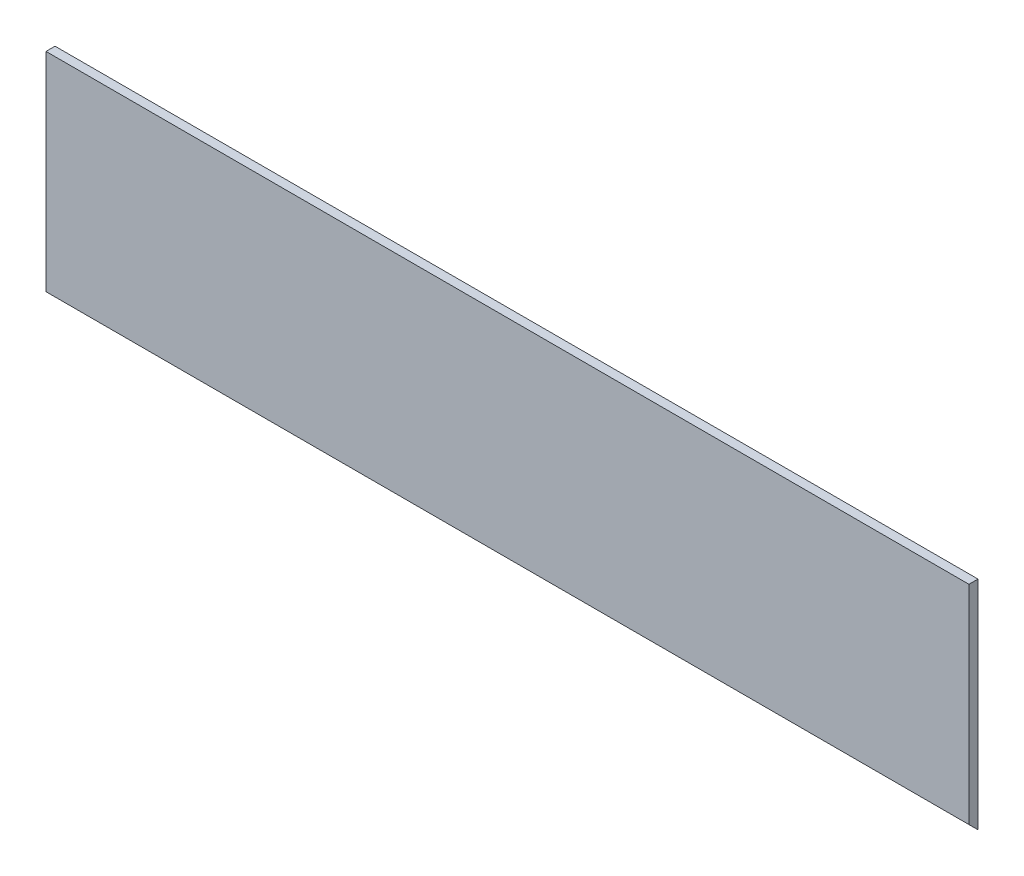
SolidWorks part; units mm, degrees
ref_plane "前视基准面" through (0, 0, 0) normal (0, 0, 1) x (1, 0, 0)
ref_plane "上视基准面" through (0, 0, 0) normal (0, 1, 0) x (1, 0, 0)
ref_plane "右视基准面" through (0, 0, 0) normal (1, 0, 0) x (0, 0, -1)
other "Configuration Table"
sketch "草图1" plane through (0, 0, 0) normal (0, 0, 1) x (1, 0, 0)
  line L1 (102, -24) -> (-102, -24)
  line L2 (102, -24) -> (102, 24)
  line L3 (102, 24) -> (-102, 24)
  line L4 (-102, -24) -> (-102, 24)
  line L5 (102, -24) -> (-102, 24) construction
  line L6 (102, 24) -> (-102, -24) construction
  point P0 (0, 0)
  dimension "D1" = 204
  dimension "D2" = 48
extrude "凸台-拉伸1" add sketch "草图1" along normal blind 2
sketch "草图2" plane through (102, 0, 0) normal (1, 0, 0) x (0, 0, -1)
  line L0 (0, -24) -> (-2, -24)
  line L1 (-2, -24) -> (-2, -22)
  line L2 (-2, -24) -> (-2, 24) construction
  line L3 (-2, -22) -> (0, -24)
  dimension "D1" = 2
extrude "切除-拉伸1" cut sketch "草图2" against normal blind 284
